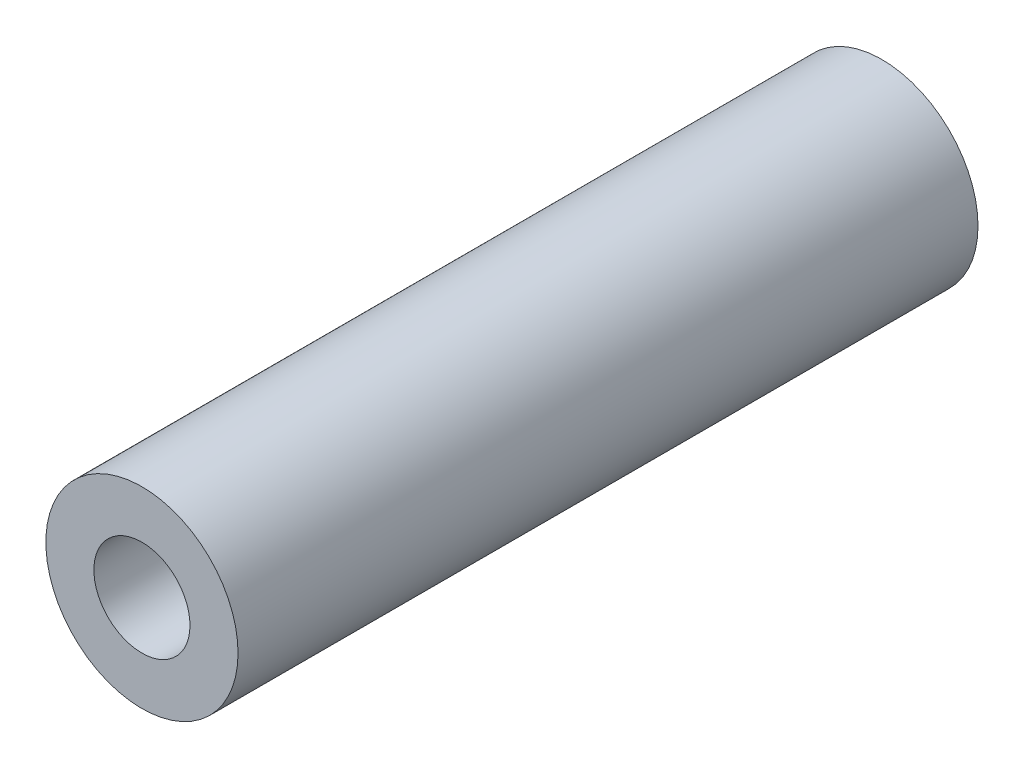
SolidWorks part; units mm, degrees
ref_plane "前视基准面" through (0, 0, 0) normal (0, 0, 1) x (1, 0, 0)
ref_plane "上视基准面" through (0, 0, 0) normal (0, 1, 0) x (1, 0, 0)
ref_plane "右视基准面" through (0, 0, 0) normal (1, 0, 0) x (0, 0, -1)
sketch "草图1" plane through (0, 0, 0) normal (0, 0, 1) x (1, 0, 0)
  circle A0 centre (0, 0) radius 3
  dimension "D1" = 6
extrude "凸台-拉伸1" add sketch "草图1" along normal blind 23.1
sketch "草图2" plane through (0, 0, 23.1) normal (0, 0, 1) x (1, 0, 0)
  circle A0 centre (0, 0) radius 1.5
  dimension "D1" = 3
extrude "切除-拉伸1" cut sketch "草图2" against normal through all
